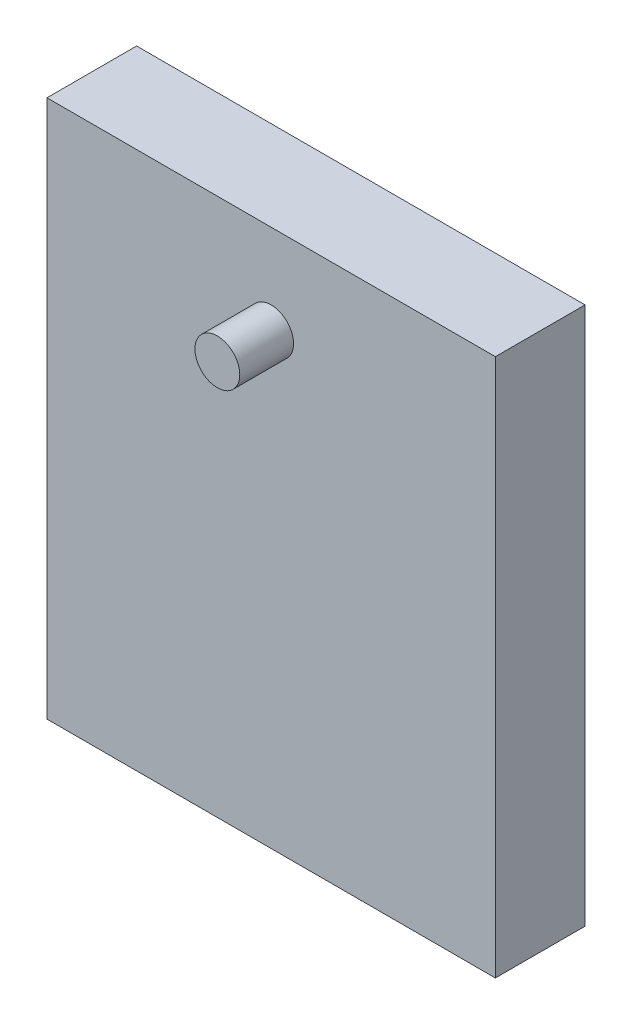
SolidWorks part; units mm, degrees
ref_plane "Plan de face" through (0, 0, 0) normal (0, 0, 1) x (1, 0, 0)
ref_plane "Plan de dessus" through (0, 0, 0) normal (0, 1, 0) x (1, 0, 0)
ref_plane "Plan de droite" through (0, 0, 0) normal (1, 0, 0) x (0, 0, -1)
sketch "Esquisse1" plane through (0, 0, 0) normal (0, 0, 1) x (1, 0, 0)
  line L1 (-30.6444, 41.5015) -> (19.3556, 41.5015)
  line L2 (-30.6444, 41.5015) -> (-30.6444, -18.4985)
  line L3 (-30.6444, -18.4985) -> (19.3556, -18.4985)
  line L4 (19.3556, 41.5015) -> (19.3556, -18.4985)
  dimension "D1" = 60
  dimension "D2" = 50
extrude "Boss.-Extru.1" add sketch "Esquisse1" along normal blind 10
sketch "Esquisse2" plane through (0, 0, 10) normal (0, 0, 1) x (1, 0, 0)
  line L0 (19.3556, 41.5015) -> (-30.6444, 41.5015) construction
  line L1 (19.3556, -18.4985) -> (19.3556, 41.5015) construction
  circle A0 centre (-5.6444, 31.5015) radius 2.5
  point P6 (-81.7473, 32.2961)
  dimension "D1" = 5
  dimension "D2" = 10
  dimension "D3" = 25
extrude "Boss.-Extru.2" add sketch "Esquisse2" along normal blind 6
